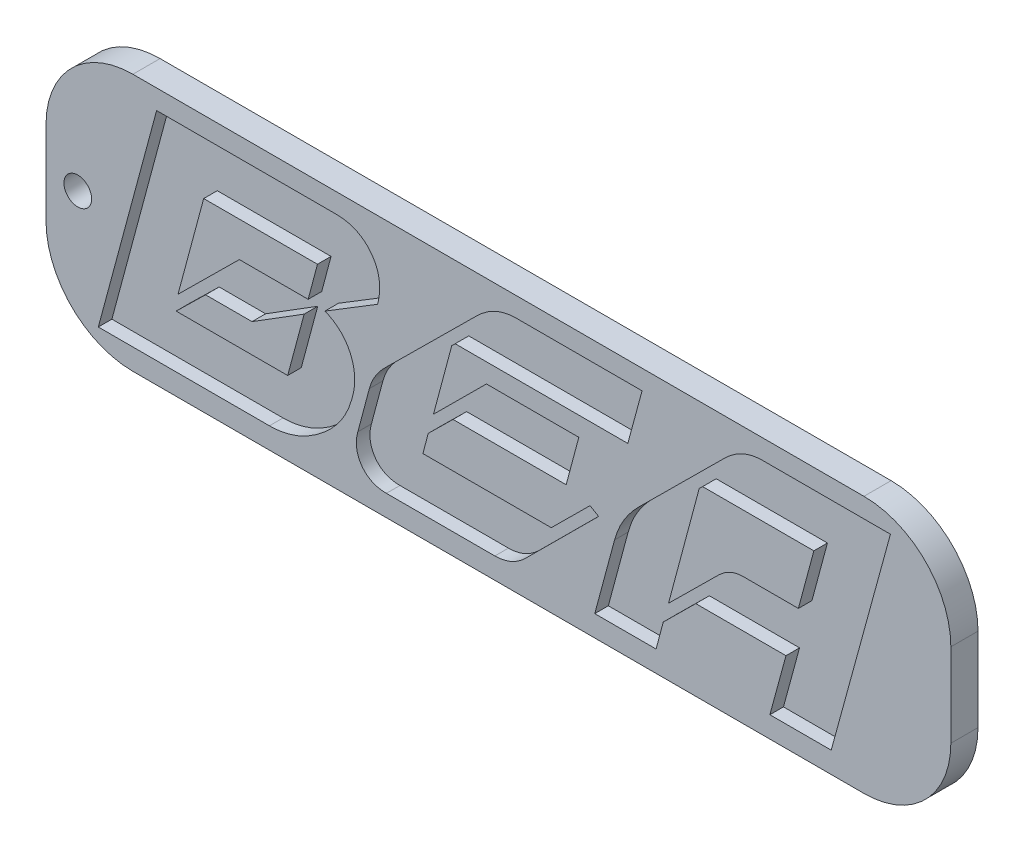
SolidWorks part; units mm, degrees
ref_plane "Front Plane" through (0, 0, 0) normal (0, 0, 1) x (1, 0, 0)
ref_plane "Top Plane" through (0, 0, 0) normal (0, 1, 0) x (1, 0, 0)
ref_plane "Right Plane" through (0, 0, 0) normal (1, 0, 0) x (0, 0, -1)
sketch "Sketch1" plane through (0, 0, 0) normal (0, 0, 1) x (1, 0, 0)
  line L0 (-7.7835, 12.6088) -> (-4.0683, 12.6088) construction
  line L1 (2.3765, 27.6508) -> (87.843, 27.6508)
  line L2 (-7.7835, 17.4908) -> (-7.7835, 7.7268)
  line L3 (2.3765, -2.4332) -> (87.843, -2.4332)
  line L4 (98.003, 17.4908) -> (98.003, 7.7268)
  circle A0 centre (-4.0683, 12.6088) radius 1.6177
  arc A1 (2.3765, 27.6508) -> (-7.7835, 17.4908) centre (2.3765, 17.4908) ccw
  arc A2 (-7.7835, 7.7268) -> (2.3765, -2.4332) centre (2.3765, 7.7268) ccw
  arc A3 (87.843, -2.4332) -> (98.003, 7.7268) centre (87.843, 7.7268) ccw
  arc A4 (87.843, 27.6508) -> (98.003, 17.4908) centre (87.843, 17.4908) cw
  text T0 "Bea" font "Sterion" height 25.4
  point P8 (100.6982, -2.4332)
  dimension "D1" = 10.16
extrude "Boss-Extrude1" add sketch "Sketch1" along normal blind 3.175
sketch "Sketch2" plane through (0, 0, 3.175) normal (0, 0, 1) x (1, 0, 0)
  text T0 "Bea" font "Sterion" height 25.4
extrude "Cut-Extrude1" cut sketch "Sketch2" against normal blind 1.5875
